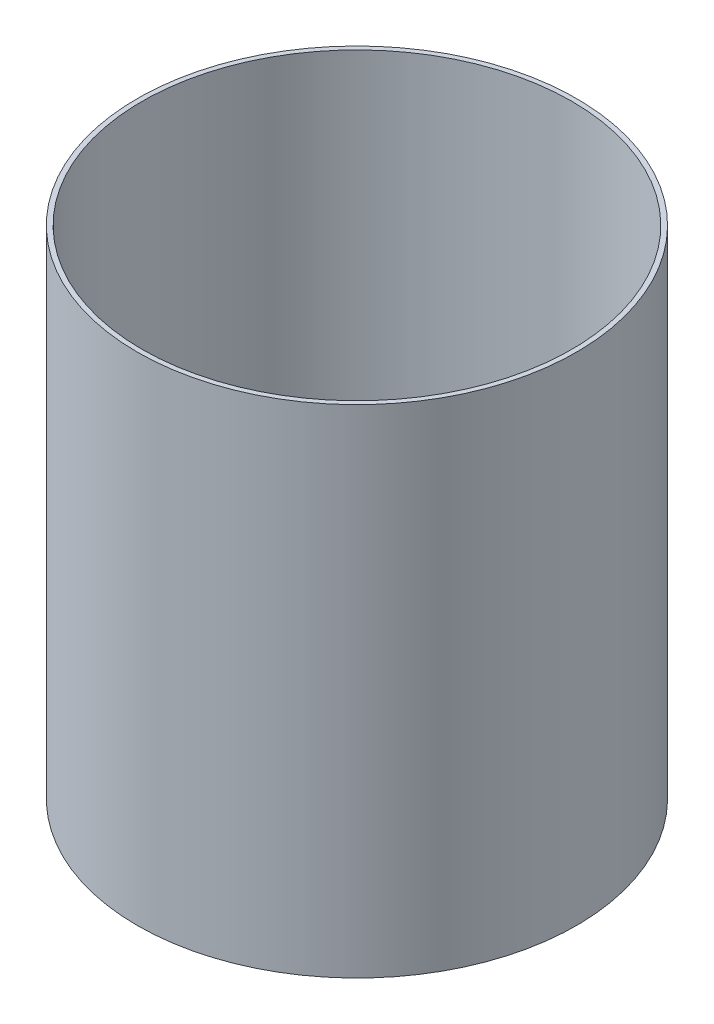
SolidWorks part; units mm, degrees
material "AISI 1035 Steel (SS)"
ref_plane "Front Plane" through (0, 0, 0) normal (0, 0, 1) x (1, 0, 0)
ref_plane "Top Plane" through (0, 0, 0) normal (0, 1, 0) x (1, 0, 0)
ref_plane "Right Plane" through (0, 0, 0) normal (1, 0, 0) x (0, 0, -1)
sketch "Sketch1" plane through (0, 0, 0) normal (0, 1, 0) x (1, 0, 0)
  circle A0 centre (0, 0) radius 690
  dimension "D1" = 1380
extrude "Boss-Extrude1" add sketch "Sketch1" along normal mid plane 1560
sketch "Sketch2" plane through (0, 0, 0) normal (0, 1, 0) x (1, 0, 0)
  circle A0 centre (0, 0) radius 675
  dimension "D1" = 1350
extrude "Cut-Extrude1" cut sketch "Sketch2" against normal through all both and the other way through all
